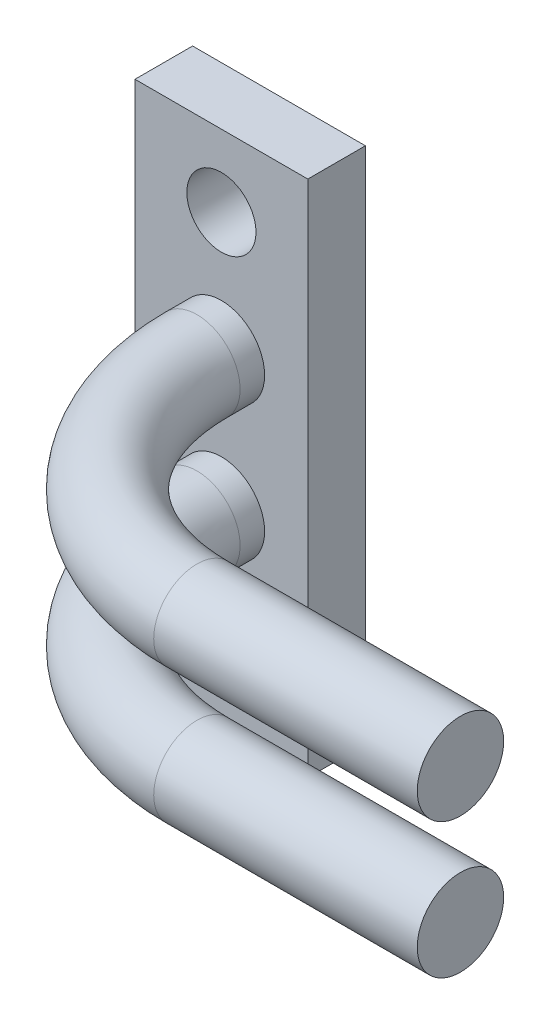
SolidWorks part; units mm, degrees
ref_plane "Front Plane" through (0, 0, 0) normal (0, 0, 1) x (1, 0, 0)
ref_plane "Top Plane" through (0, 0, 0) normal (0, 1, 0) x (1, 0, 0)
ref_plane "Right Plane" through (0, 0, 0) normal (1, 0, 0) x (0, 0, -1)
sketch "Sketch1" plane through (0, 0, 0) normal (0, 0, 1) x (1, 0, 0)
  line L1 (-3, -9) -> (3, -9)
  line L2 (-3, -9) -> (-3, 9)
  line L3 (-3, 9) -> (3, 9)
  line L4 (3, -9) -> (3, 9)
  line L5 (-3, -9) -> (3, 9) construction
  line L6 (-3, 9) -> (3, -9) construction
  point P0 (0, 0)
  dimension "D1" = 18
  dimension "D2" = 6
extrude "Boss-Extrude1" add sketch "Sketch1" along normal blind 2
sketch "Sketch2" plane through (0, 0, 0) normal (0, 0, -1) x (-1, 0, 0)
  circle A0 centre (0, 2.35) radius 1.5
  circle A1 centre (0, -2.35) radius 1.5
  dimension "D2" = 3
  dimension "D1" = 4.7
  dimension "D3" = 2.35
extrude "Boss-Extrude2" add sketch "Sketch2" along normal blind 2.1
fillet "Fillet1" radius 1.5 2 edges at (-1.5, -2.35, -2.1) (-1.5, 2.35, -2.1)
sketch "Sketch3" plane through (0, 0, 2) normal (0, 0, 1) x (1, 0, 0)
  circle A0 centre (0, -2.35) radius 1.5 construction
  circle A1 centre (0, 2.35) radius 1.5 construction
  circle A2 centre (0, -2.35) radius 1.5
  circle A3 centre (0, 2.35) radius 1.5
ref_plane "Plane1" through (0, 2.35, 0) normal (0, 1, 0) x (-1, 0, 0)
sketch "Sketch4" plane through (0, 2.35, 0) normal (0, 1, 0) x (-1, 0, 0)
  line L0 (0, 2) -> (0, 2.85)
  line L1 (1.5, 2) -> (-1.5, 2) construction
  line L2 (-7.5, 10.35) -> (-16.65, 10.35)
  arc A0 (0, 2.85) -> (-7.5, 10.35) centre (-7.5, 2.85) ccw
  point P8 (0, 10.35)
  dimension "D3" = 7.5
  dimension "D1" = 16.65
  dimension "D2" = 8.35
sweep "Sweep1" add profiles "Sketch3" path "Sketch4"
sketch "Sketch5" plane through (0, 0, 2) normal (0, 0, 1) x (1, 0, 0)
  line L0 (0, 0) -> (0, 6.5) construction
  line L1 (0, 0) -> (3, 0) construction
  line L2 (3, -9) -> (3, 9) construction
  line L3 (3, 9) -> (-3, 9) construction
  circle A0 centre (0, 6.5) radius 1.2
  circle A1 centre (0, -6.5) radius 1.2
  dimension "D1" = 2.4
  dimension "D2" = 2.5
extrude "Cut-Extrude1" cut sketch "Sketch5" against normal through all
